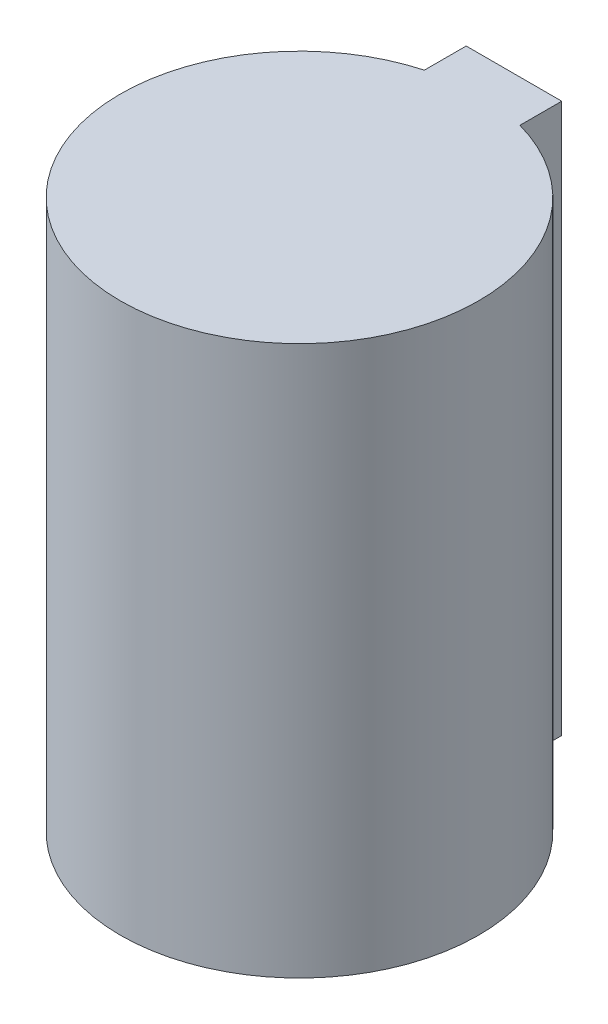
SolidWorks part; units mm, degrees
ref_plane "Plano frontal" through (0, 0, 0) normal (0, 0, 1) x (1, 0, 0)
ref_plane "Plano superior" through (0, 0, 0) normal (0, 1, 0) x (1, 0, 0)
ref_plane "Plano direito" through (0, 0, 0) normal (1, 0, 0) x (0, 0, -1)
sketch "Esboço1" plane through (0, 0, 0) normal (0, 1, 0) x (1, 0, 0)
  line L1 (-2, 8.9784) -> (2, 8.9784)
  line L2 (-2, 8.9784) -> (-2, 7.2284)
  line L4 (2, 8.9784) -> (2, 7.2284)
  arc A0 (-2, 7.2284) -> (2, 7.2284) centre (0, 0) ccw
  point P1 (5.6365, 5.9934)
  point P7 (0, 0)
  point P8 (0, 0)
  dimension "D1" = 15
  dimension "D2" = 4
  dimension "D3" = 1.75
  dimension "D4" = 2
extrude "Ressalto-extrusão1" add sketch "Esboço1" along normal blind 23
